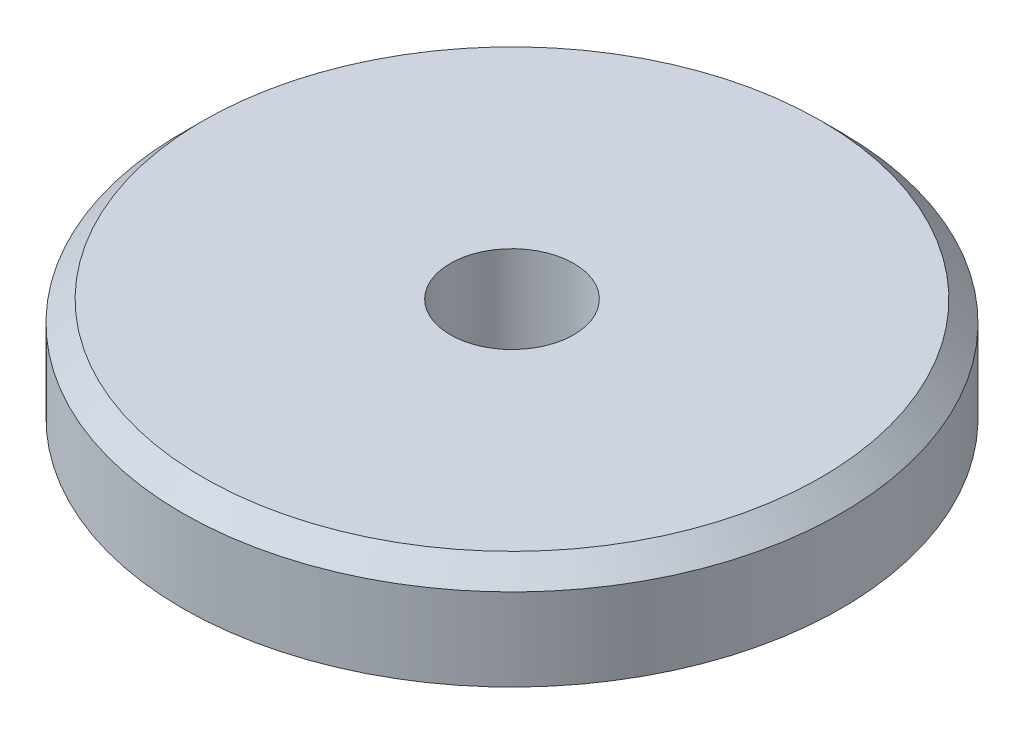
SolidWorks part; units mm, degrees
ref_plane "Спереди" through (0, 0, 0) normal (0, 0, 1) x (1, 0, 0)
ref_plane "Сверху" through (0, 0, 0) normal (0, 1, 0) x (1, 0, 0)
ref_plane "Справа" through (0, 0, 0) normal (1, 0, 0) x (0, 0, -1)
sketch "Эскиз1" plane through (0, 0, 0) normal (0, 0, 1) x (1, 0, 0)
  line L0 (-3, -1.0692) -> (-16, -1.0692)
  line L1 (-16, -1.0692) -> (-16, 2.9308)
  line L2 (-15, 3.9308) -> (-3, 3.9308)
  line L4 (0, 0) -> (0, 15.6005) construction
  line L5 (0, 15.6005) -> (0, -12.6951) construction
  line L6 (-3, 3.9308) -> (-3, -1.0692)
  line L7 (-16, 2.9308) -> (-15, 3.9308)
  point P4 (-16, 3.9308)
  point P9 (-16, 1.8964)
  point P11 (-16, 1.9747)
  point P12 (-15, 0.9308)
  point P14 (-14.9797, 2.1313)
  dimension "D1" = 16
  dimension "D2" = 3
  dimension "D3" = 5
  dimension "D4" = 1
  dimension "D5" = 45
revolve "Повернуть1" add sketch "Эскиз1" angle 360 about L4
